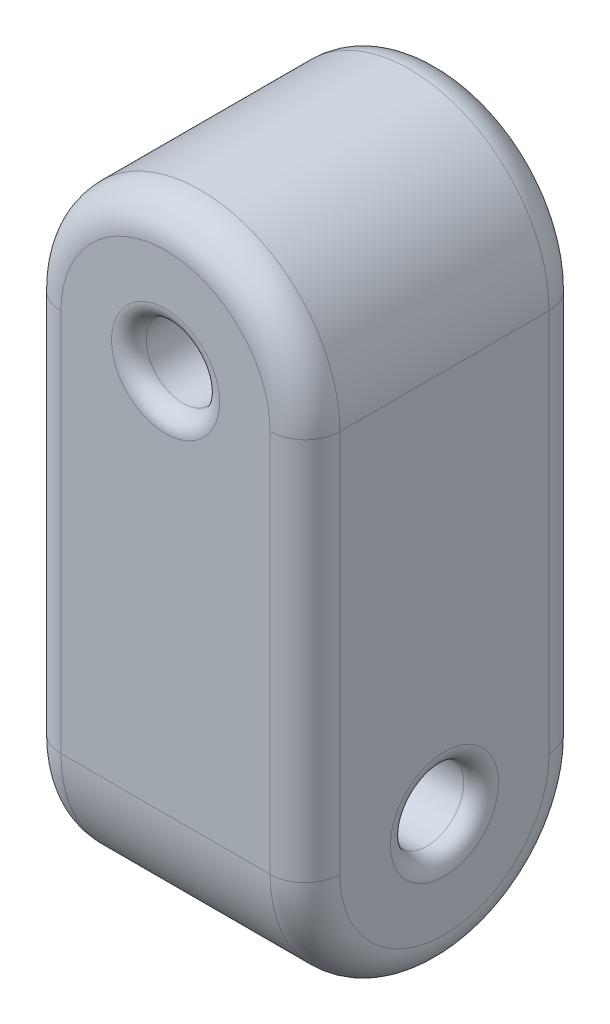
SolidWorks part; units mm, degrees
ref_plane "Front Plane" through (0, 0, 0) normal (0, 0, 1) x (1, 0, 0)
ref_plane "Top Plane" through (0, 0, 0) normal (0, 1, 0) x (1, 0, 0)
ref_plane "Right Plane" through (0, 0, 0) normal (1, 0, 0) x (0, 0, -1)
sketch "Sketch1" plane through (0, 0, 0) normal (0, 0, 1) x (1, 0, 0)
  circle A0 centre (0, 0) radius 1.05
sketch "Sketch2" plane through (0, 0, 0) normal (0, 0, 1) x (1, 0, 0)
  circle A0 centre (0, 0) radius 4
extrude "Boss-Extrude1" add sketch "Sketch2" along normal blind 8 from offset 0.8
sketch "Sketch7" plane through (0, 0, 0.8) normal (0, 0, -1) x (-1, 0, 0)
  line L0 (0, 0) -> (0, -18) construction
  dimension "D1" = 18
sketch "Sketch8" plane through (0, 0, 0) normal (1, 0, 0) x (0, 0, -1)
  circle A0 centre (-4.8, -11) radius 4
  dimension "D1" = 11
sketch "Sketch9" plane through (0, 0, 0) normal (1, 0, 0) x (0, 0, -1)
  circle A0 centre (-4.8, -11) radius 1.05
  dimension "D1" = 11
sketch "Sketch10" plane through (0, 0, 0.8) normal (0, 0, -1) x (-1, 0, 0)
  line L1 (-4, 0) -> (4, 0)
  line L2 (-4, 0) -> (-4, -11)
  line L3 (-4, -11) -> (4, -11)
  line L4 (4, 0) -> (4, -11)
  circle A0 centre (0, 0) radius 4 construction
  dimension "D1" = 11
extrude "Boss-Extrude2" add sketch "Sketch10" against normal blind 8 contours L4 L3 L2 L1
extrude "Boss-Extrude3" add sketch "Sketch8" against normal blind 8 from offset 4 contours A0
extrude "Cut-Extrude2" cut sketch "Sketch1" along normal blind 9.6 contours A0
extrude "Cut-Extrude3" cut sketch "Sketch9" against normal blind 9.95 from offset 4.975
fillet "Fillet1" radius 1 8 edges at (4, -5.5, 8.8) (4, -5.5, 0.8) (4, -15, 4.8) (-4, -5.5, 0.8) (-4, -5.5, 8.8) (-4, -15, 4.8) (0, 4, 8.8) (0, 4, 0.8)
fillet "Fillet2" radius 0.5 4 edges at (1.05, 0, 8.8) (1.05, 0, 0.8) (-4, -9.95, 4.8) (4, -9.95, 4.8)
